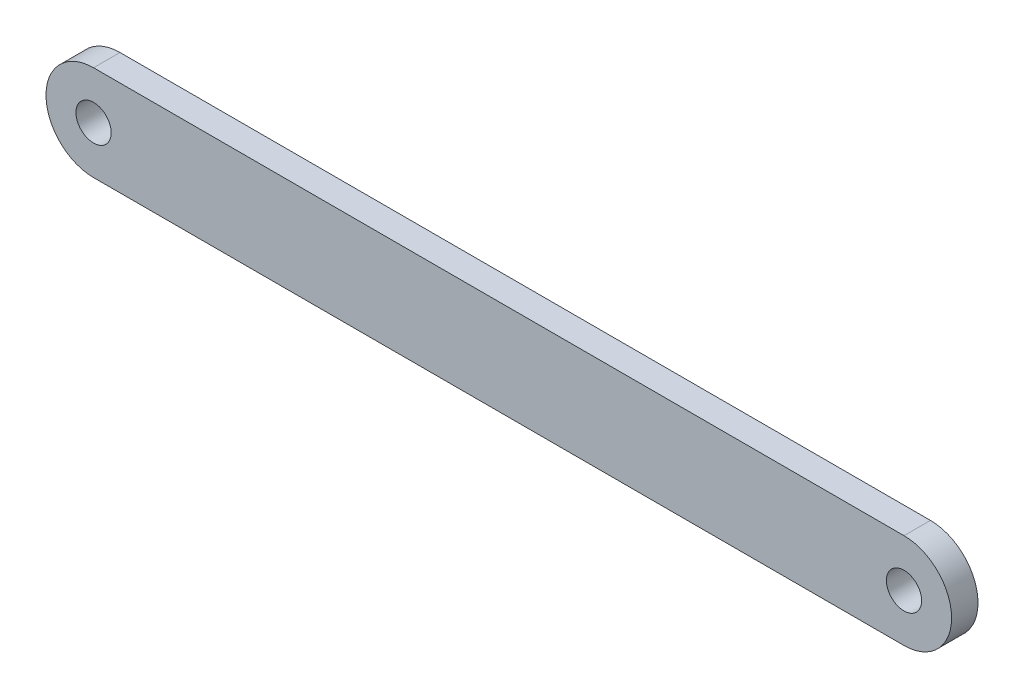
SolidWorks part; units mm, degrees
material "6061 Alloy"
ref_plane "Front Plane" through (0, 0, 0) normal (0, 0, 1) x (1, 0, 0)
ref_plane "Top Plane" through (0, 0, 0) normal (0, 1, 0) x (1, 0, 0)
ref_plane "Right Plane" through (0, 0, 0) normal (1, 0, 0) x (0, 0, -1)
sketch "Sketch2" plane through (0, 0, 0) normal (0, 0, 1) x (1, 0, 0)
  line L0 (0, 0) -> (0, 85672.5492) construction
  line L1 (0, 0) -> (85672.5492, 0) construction
  line L2 (-230, 27) -> (230, 27)
  line L3 (-230, -27) -> (230, -27)
  arc A0 (230, 27) -> (230, -27) centre (230, 0) cw
  arc A1 (-230, 27) -> (-230, -27) centre (-230, 0) ccw
  circle A2 centre (-230, 0) radius 10
  circle A3 centre (230, 0) radius 10
  point P8 (0, 27)
  dimension "D3" = 20
  dimension "D1" = 460
  dimension "D2" = 54
extrude "Boss-Extrude2" add sketch "Sketch2" against normal blind 15
